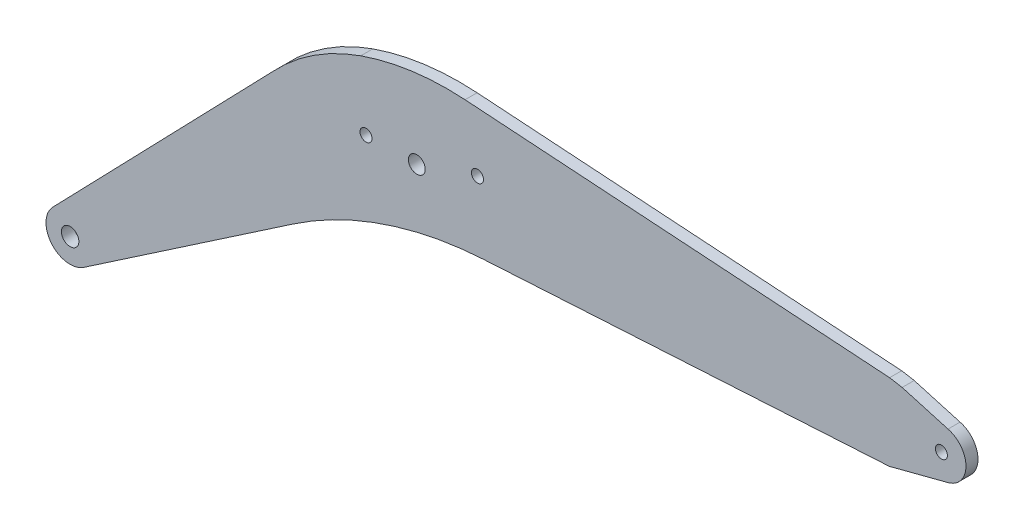
SolidWorks part; units mm, degrees
ref_plane "Front Plane" through (0, 0, 0) normal (0, 0, 1) x (1, 0, 0)
ref_plane "Top Plane" through (0, 0, 0) normal (0, 1, 0) x (1, 0, 0)
ref_plane "Right Plane" through (0, 0, 0) normal (1, 0, 0) x (0, 0, -1)
sketch "Sketch1" plane through (0, 0, 0) normal (0, 0, 1) x (1, 0, 0)
  line L0 (-128.1736, 10.2934) -> (-76.0452, 45.7065)
  line L1 (-28.7952, 61.7565) -> (72.2572, 67.6424)
  line L2 (72.2572, 67.6424) -> (86.8536, 71.4375)
  line L3 (86.8536, 82.9755) -> (75.4435, 86.2366)
  line L4 (75.4435, 86.2366) -> (72.3241, 86.7806)
  line L5 (72.3241, 86.7806) -> (-33.2952, 93.8565)
  line L6 (-81.1452, 76.0065) -> (-135.8584, 19.4274)
  arc A0 (-76.0452, 45.7065) -> (-28.7952, 61.7565) centre (-23.3417, -31.8737) cw
  arc A1 (86.8536, 71.4375) -> (86.8536, 82.9755) centre (85.3537, 77.2065) ccw
  arc A2 (-33.2952, 93.8565) -> (-59.24, 90.3458) centre (-37.6697, 28.5604) ccw
  arc A3 (-59.24, 90.3458) -> (-81.1452, 76.0065) centre (-41.3598, 39.1301) ccw
  arc A4 (-135.8584, 19.4274) -> (-128.1736, 10.2934) centre (-131.5452, 15.2565) ccw
  circle A5 centre (85.2048, 77.2065) radius 1.5
  circle A6 centre (-45.2952, 73.9112) radius 2.1
  circle A7 centre (-131.5452, 15.2565) radius 2.175
  circle A9 centre (-57.9271, 73.9112) radius 1.5
  circle A10 centre (-30.211, 78.9466) radius 1.5
  dimension "D1" = 4.35
  dimension "D2" = 4.2
  dimension "D3" = 3
  dimension "D4" = 3
  dimension "D5" = 3
extrude "Boss-Extrude3" add sketch "Sketch1" along normal blind 3
ref_plane "Plane1" through (-33.2952, 93.8565, 3) normal (-0.9978, 0.0668, 0) x (0, 0, 1)
